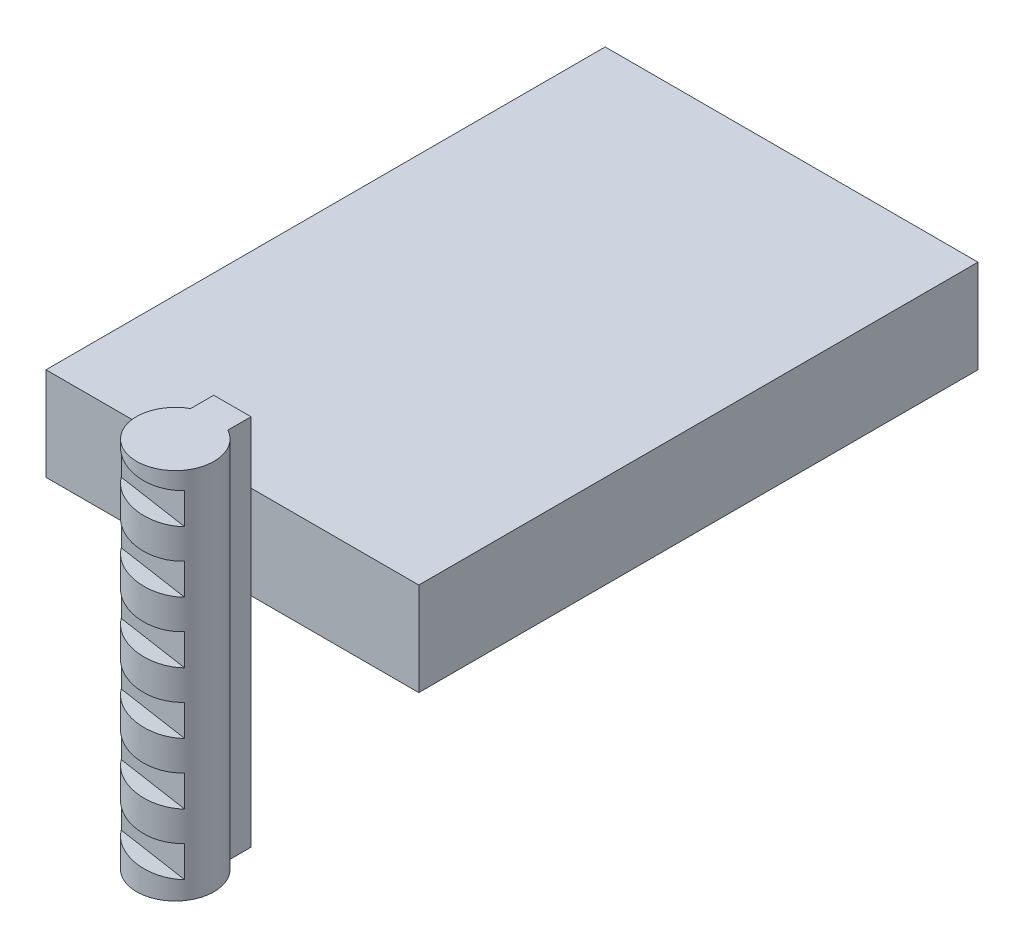
SolidWorks part; units mm, degrees
ref_plane "Front Plane" through (0, 0, 0) normal (0, 0, 1) x (1, 0, 0)
ref_plane "Top Plane" through (0, 0, 0) normal (0, 1, 0) x (1, 0, 0)
ref_plane "Right Plane" through (0, 0, 0) normal (1, 0, 0) x (0, 0, -1)
sketch "Sketch1" plane through (0, 0, 0) normal (0, 1, 0) x (1, 0, 0)
  line L0 (0, 0) -> (0, 2.6411) construction
  line L2 (-1.27, 3.892) -> (1.27, 3.892)
  line L3 (-1.27, 3.892) -> (-1.27, 2.3157)
  line L5 (1.27, 3.892) -> (1.27, 2.3157)
  line L6 (-1.27, 3.892) -> (2.6293, 0.0513) construction
  line L7 (-2.6293, 0.0513) -> (1.27, 3.892) construction
  arc A0 (-1.27, 2.3157) -> (1.27, 2.3157) centre (0, 0) ccw
  dimension "D1" = 2.54
  dimension "D2" = 1.5763
extrude "Boss-Extrude1" add sketch "Sketch1" along normal blind 25.4
sketch "Sketch3" plane through (0, 0, -3.892) normal (0, 0, -1) x (-1, 0, 0)
  line L0 (0, 0) -> (0, 25.4) construction
  line L1 (-12.7, 21.1861) -> (12.7, 21.1861)
  line L2 (-12.7, 21.1861) -> (-12.7, 14.8361)
  line L3 (-12.7, 14.8361) -> (12.7, 14.8361)
  line L4 (12.7, 21.1861) -> (12.7, 14.8361)
  line L5 (-12.7, 21.1861) -> (12.7, 14.8361) construction
  line L6 (-12.7, 14.8361) -> (12.7, 21.1861) construction
  line L7 (-1.27, 0) -> (1.27, 0) construction
  line L8 (-1.27, 25.4) -> (1.27, 25.4) construction
  point P0 (0, 18.0111)
  dimension "D1" = 25.4
  dimension "D2" = 6.35
extrude "Boss-Extrude3" add sketch "Sketch3" along normal blind 38.1
sketch "Sketch4" plane through (0, 0, 0) normal (0, 0, 1) x (1, 0, 0)
  line L0 (-3.1135, 25.0013) -> (-3.1135, 23.1217)
  line L1 (-3.1135, 23.1217) -> (2.8764, 22.0655)
  line L2 (-3.1135, 25.0013) -> (2.8764, 23.9451)
  line L3 (2.8764, 23.9451) -> (2.8764, 22.0655)
  line L4 (-3.1135, 16.6701) -> (-3.1135, 14.7905)
  line L5 (-3.1135, 14.7905) -> (2.8764, 13.7343)
  line L6 (-3.1135, 16.6701) -> (2.8764, 15.6139)
  line L7 (2.8764, 15.6139) -> (2.8764, 13.7343)
  line L12 (-3.1135, 20.8357) -> (-3.1135, 18.9561)
  line L13 (-3.1135, 18.9561) -> (2.8764, 17.8999)
  line L14 (-3.1135, 20.8357) -> (2.8764, 19.7795)
  line L15 (2.8764, 19.7795) -> (2.8764, 17.8999)
  line L16 (-3.1135, 12.5045) -> (-3.1135, 10.6249)
  line L17 (-3.1135, 10.6249) -> (2.8764, 9.5687)
  line L18 (-3.1135, 12.5045) -> (2.8764, 11.4483)
  line L19 (2.8764, 11.4483) -> (2.8764, 9.5687)
  line L20 (-3.1135, 8.3389) -> (-3.1135, 6.4593)
  line L21 (-3.1135, 6.4593) -> (2.8764, 5.4031)
  line L22 (-3.1135, 8.3389) -> (2.8764, 7.2827)
  line L23 (2.8764, 7.2827) -> (2.8764, 5.4031)
  line L24 (-3.1135, 4.1733) -> (-3.1135, 2.2937)
  line L25 (-3.1135, 2.2937) -> (2.8764, 1.2375)
  line L26 (-3.1135, 4.1733) -> (2.8764, 3.1171)
  line L27 (2.8764, 3.1171) -> (2.8764, 1.2375)
  line L36 (2.8764, 17.8999) -> (2.8764, 15.6139) construction
  line L38 (2.8764, 13.7343) -> (2.8764, 11.4483) construction
  line L40 (2.8764, 9.5687) -> (2.8764, 7.2827) construction
  line L42 (2.8764, 5.4031) -> (2.8764, 3.1171) construction
  line L47 (2.8764, 22.0655) -> (2.8764, 19.7795) construction
  dimension "D1" = 100
  dimension "D2" = 1.8796
  dimension "D3" = 2.286
extrude "Cut-Extrude1" cut sketch "Sketch4" against normal blind 3.556 draft 2 from offset 5.08
